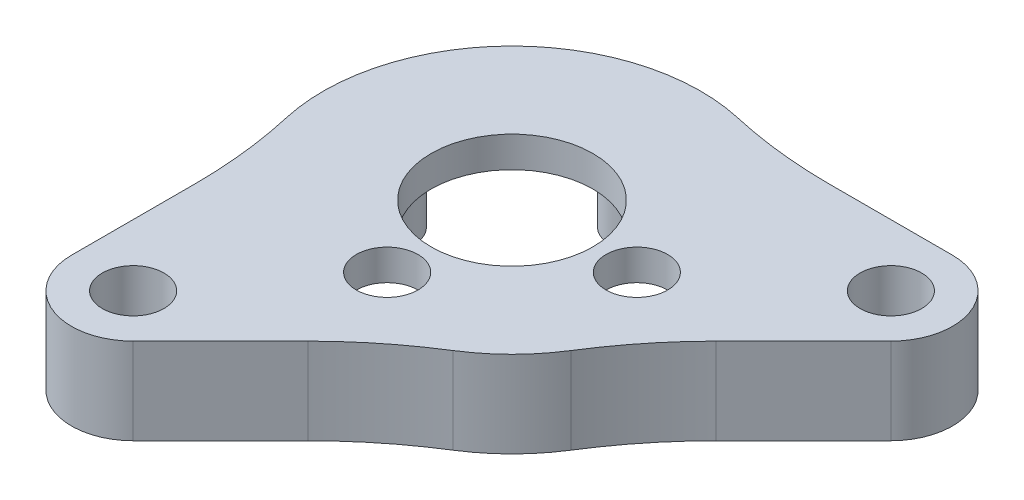
SolidWorks part; units mm, degrees
ref_plane "Front Plane" through (0, 0, 0) normal (0, 0, 1) x (1, 0, 0)
ref_plane "Top Plane" through (0, 0, 0) normal (0, 1, 0) x (1, 0, 0)
ref_plane "Right Plane" through (0, 0, 0) normal (1, 0, 0) x (0, 0, -1)
sketch "Sketch1" plane through (0, 0, 0) normal (0, 1, 0) x (1, 0, 0)
  line L0 (0, 11.2) -> (17.3823, 11.2)
  line L1 (20.2108, 4.3716) -> (-4.3716, -20.2108)
  line L2 (0, 0) -> (7.9196, -7.9196) construction
  line L3 (-11.2, 0) -> (-11.2, -17.3823)
  circle A0 centre (0, 0) radius 11.2
  arc A1 (17.3823, 11.2) -> (20.2108, 4.3716) centre (17.3823, 7.2) cw
  arc A2 (-11.2, -17.3823) -> (-4.3716, -20.2108) centre (-7.2, -17.3823) ccw
  circle A3 centre (0, 0) radius 12.25
  dimension "D1" = 22.4
  dimension "D2" = 4
  dimension "D4" = 24.5
  dimension "D3" = 45
extrude "Boss-Extrude7" add sketch "Sketch1" along normal blind 3.6 contours A3 L3 A2 L1 | L3 A3 L1 A0 | L1 A3 | L1 A3 L0 A0 | A3 L1 A1 L0 | L0 A3 L3 A0
sketch "Sketch3" plane through (0, 3.6, 0) normal (0, 1, 0) x (1, 0, 0)
  line L4 (11.4283, -4.4109) -> (20.2108, 4.3716)
  line L5 (17.3823, 11.2) -> (4.9621, 11.2)
  line L6 (-11.2, -4.9621) -> (-11.2, -17.3823)
  line L7 (-4.3716, -20.2108) -> (4.4109, -11.4283)
  line L8 (11.4283, -4.4109) -> (20.2108, 4.3716)
  line L9 (17.3823, 11.2) -> (4.9621, 11.2)
  line L10 (-11.2, -4.9621) -> (-11.2, -17.3823)
  line L11 (-4.3716, -20.2108) -> (4.4109, -11.4283)
  arc A0 (4.9621, 11.2) -> (-11.2, -4.9621) centre (0, 0) ccw
  circle A1 centre (0, 0) radius 5.25
  arc A2 (4.9621, 11.2) -> (-11.2, -4.9621) centre (0, 0) ccw construction
  arc A3 (4.4109, -11.4283) -> (11.4283, -4.4109) centre (0, 0) ccw
  arc A7 (4.4109, -11.4283) -> (11.4283, -4.4109) centre (0, 0) ccw
  arc A8 (20.2108, 4.3716) -> (17.3823, 11.2) centre (17.3823, 7.2) ccw
  arc A9 (4.9621, 11.2) -> (-11.2, -4.9621) centre (0, 0) ccw
  arc A10 (-11.2, -17.3823) -> (-4.3716, -20.2108) centre (-7.2, -17.3823) ccw
  arc A11 (4.4109, -11.4283) -> (11.4283, -4.4109) centre (0, 0) ccw
  arc A12 (20.2108, 4.3716) -> (17.3823, 11.2) centre (17.3823, 7.2) ccw
  arc A13 (4.9621, 11.2) -> (-11.2, -4.9621) centre (0, 0) ccw
  arc A14 (-11.2, -17.3823) -> (-4.3716, -20.2108) centre (-7.2, -17.3823) ccw
  arc M3 (4.4109, -11.4283) -> (11.4283, -4.4109) centre (0, 0) ccw
  line M4 (11.4283, -4.4109) -> (20.2108, 4.3716)
  arc M5 (20.2108, 4.3716) -> (17.3823, 11.2) centre (17.3823, 7.2) ccw
  line M6 (17.3823, 11.2) -> (4.9621, 11.2)
  arc M7 (4.9621, 11.2) -> (-11.2, -4.9621) centre (0, 0) ccw
  line M8 (-11.2, -4.9621) -> (-11.2, -17.3823)
  arc M9 (-11.2, -17.3823) -> (-4.3716, -20.2108) centre (-7.2, -17.3823) ccw
  line M10 (-4.3716, -20.2108) -> (4.4109, -11.4283)
  circle M11 centre (0, 0) radius 11.2
  dimension "D1" = 10.5
  dimension "D2" = 0
extrude "Boss-Extrude8" add sketch "Sketch3" along normal blind 2 contours A1 M11 | M10 M3 M4 M5 M6 M7 M8 M9 M11
sketch "Sketch4" plane through (0, 0, 0) normal (0, 1, 0) x (1, 0, 0)
  circle A0 centre (-7.2, -17.3823) radius 2
  circle A1 centre (17.3823, 7.2) radius 2
  arc A4 (20.2108, 4.3716) -> (17.3823, 11.2) centre (17.3823, 7.2) ccw construction
  arc A5 (-11.2, -17.3823) -> (-4.3716, -20.2108) centre (-7.2, -17.3823) ccw construction
  dimension "D1" = 4
  dimension "D2" = 4
extrude "Cut-Extrude1" cut sketch "Sketch4" along normal through all
fillet "Fillet5" radius 30 4 edges at (4.9621, 2.8, -11.2) (-11.2, 2.8, 4.9621) (4.4109, 2.8, 11.4283) (11.4283, 2.8, 4.4109)
sketch "Sketch5" plane through (0, 3.6, 0) normal (0, -1, 0) x (1, 0, 0)
  line L0 (0, 0) -> (0, -5.25) construction
  line L1 (0, 0) -> (5.25, 0) construction
  line L2 (-3.7123, -3.7123) -> (0, 0) construction
  line L3 (0, 0) -> (-8.1, 0) construction
  circle A0 centre (-8.1, 0) radius 1.8
  circle A1 centre (0, 0) radius 5.25 construction
  circle A2 centre (8.1, 0) radius 1.8
  circle A3 centre (0, -8.1) radius 1.8
  circle A4 centre (0, 8.1) radius 1.8
  dimension "D1" = 3.6
  dimension "D2" = 8.1
  dimension "D3" = 45
extrude "Boss-Extrude9" add sketch "Sketch5" along normal up to surface (3.6 mm away) up to face at (-7.2, 0, 19.3823)
sketch "Sketch6" plane through (0, 0, 0) normal (0, -1, 0) x (1, 0, 0)
  circle A0 centre (0, 8.1) radius 2
  dimension "D1" = 4
extrude "Cut-Extrude3" cut sketch "Sketch6" against normal blind 10 contours A0
sketch "Sketch7" plane through (0, 5.6, 0) normal (0, 1, 0) x (1, 0, 0)
  arc A0 (6.5277, -10.3659) -> (10.3659, -6.5277) centre (0, 0) ccw construction
  point P0 (8.6621, -8.6621)
ref_plane "Plane1" through (0, 0, 0) normal (-0.7071, 0, 0.7071) x (0.7071, 0, 0.7071)
mirror "Mirror1" about plane through (0, 0, 0) normal (-0.7071, 0, 0.7071) of "Cut-Extrude3"
